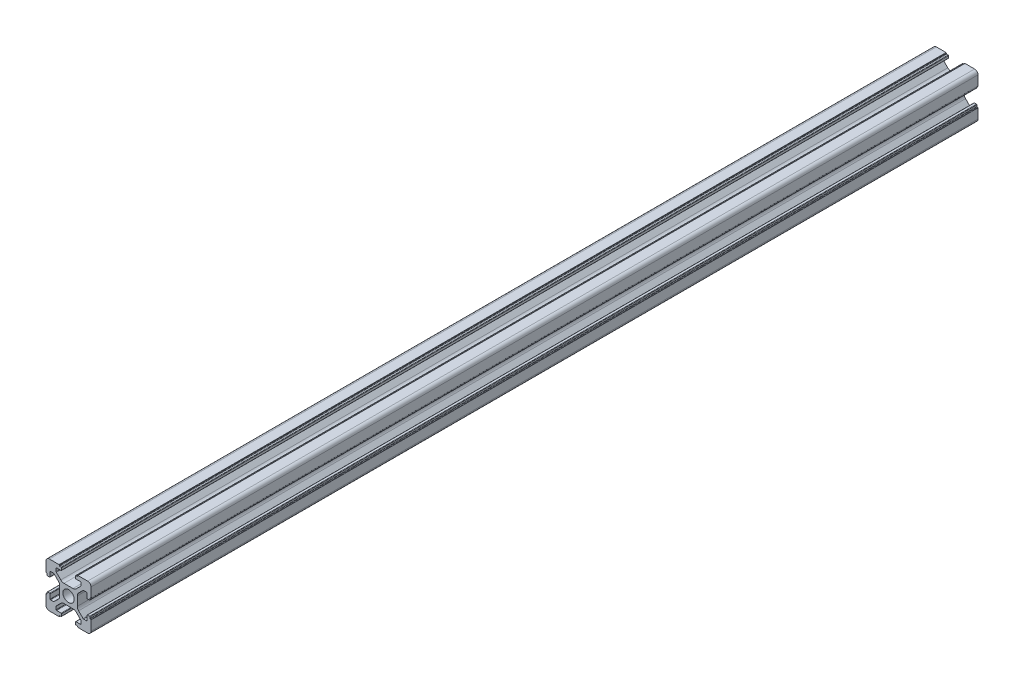
SolidWorks part; units mm, degrees
material "6063-T5"
ref_plane "Front Plane" through (0, 0, 0) normal (0, 0, 1) x (1, 0, 0)
ref_plane "Top Plane" through (0, 0, 0) normal (0, 1, 0) x (1, 0, 0)
ref_plane "Right Plane" through (0, 0, 0) normal (1, 0, 0) x (0, 0, -1)
sketch "Sketch1" plane through (0, 0, 0) normal (0, 0, -1) x (1, 0, 0)
  line L0 (1.5, 0) -> (5.8, 0)
  line L1 (20, 1.5) -> (20, 5.8)
  line L2 (18.5, 20) -> (14.2, 20)
  line L3 (0, 18.5) -> (0, 14.2)
  line L4 (14.2, 0) -> (18.5, 0)
  line L5 (13.3, 18.2) -> (15.3, 18.2)
  line L6 (20, 14.2) -> (20, 18.5)
  line L7 (0, 5.8) -> (0, 1.5)
  line L8 (6.7, 18.2) -> (4.7, 18.2)
  line L9 (1.8, 13.3) -> (1.8, 15.3)
  line L10 (19.3, 13.1) -> (18.4, 13.1)
  line L11 (19.3, 6.9) -> (18.4, 6.9)
  line L12 (6.9, 19.3) -> (6.9, 18.4)
  line L13 (13.1, 19.3) -> (13.1, 18.4)
  line L14 (0.7, 13.1) -> (1.6, 13.1)
  line L15 (0.7, 6.9) -> (1.6, 6.9)
  line L16 (13.4251, 14.4858) -> (15.4121, 16.4728)
  line L17 (14.4858, 13.4251) -> (16.4728, 15.4121)
  line L18 (14.4858, 6.5749) -> (16.4728, 4.5879)
  line L19 (13.4251, 5.5142) -> (15.4121, 3.5272)
  line L20 (6.5749, 5.5142) -> (4.5879, 3.5272)
  line L21 (5.5142, 6.5749) -> (3.5272, 4.5879)
  line L22 (5.5142, 13.4251) -> (3.5272, 15.4121)
  line L23 (6.5749, 14.4858) -> (4.5879, 16.4728)
  line L24 (6.9, 0.7) -> (6.9, 1.6)
  line L25 (13.1, 0.7) -> (13.1, 1.6)
  line L26 (5.8, 20) -> (1.5, 20)
  line L27 (1.8, 6.7) -> (1.8, 4.7)
  line L28 (6.7, 1.8) -> (4.7, 1.8)
  line L29 (13.3, 1.8) -> (15.3, 1.8)
  line L30 (18.2, 13.3) -> (18.2, 15.3)
  line L31 (18.2, 6.7) -> (18.2, 4.7)
  line L32 (2, 4.5) -> (3.3151, 4.5)
  line L33 (2, 15.5) -> (3.3151, 15.5)
  line L34 (4.5, 18) -> (4.5, 16.6849)
  line L35 (15.5, 18) -> (15.5, 16.6849)
  line L36 (18, 15.5) -> (16.6849, 15.5)
  line L37 (4.5, 2) -> (4.5, 3.3151)
  line L38 (15.5, 2) -> (15.5, 3.3151)
  line L39 (18, 4.5) -> (16.6849, 4.5)
  line L40 (7.9891, 13.9) -> (12.0109, 13.9)
  line L41 (7.9891, 6.1) -> (12.0109, 6.1)
  line L42 (13.9, 12.0109) -> (13.9, 7.9891)
  line L43 (6.1, 12.0109) -> (6.1, 7.9891)
  line L44 (19.5, 6.7) -> (19.5, 6.1)
  line L45 (5.9, 19.9) -> (5.9, 19.7)
  line L46 (6.1, 19.5) -> (6.7, 19.5)
  line L47 (14.1, 19.9) -> (14.1, 19.7)
  line L48 (13.9, 19.5) -> (13.3, 19.5)
  line L49 (0.1, 14.1) -> (0.3, 14.1)
  line L50 (0.5, 13.9) -> (0.5, 13.3)
  line L51 (0.1, 5.9) -> (0.3, 5.9)
  line L52 (0.5, 6.1) -> (0.5, 6.7)
  line L53 (19.9, 14.1) -> (19.7, 14.1)
  line L54 (19.5, 13.9) -> (19.5, 13.3)
  line L55 (19.7, 5.9) -> (19.9, 5.9)
  line L56 (14.1, 0.1) -> (14.1, 0.3)
  line L57 (13.9, 0.5) -> (13.3, 0.5)
  line L58 (6.7, 0.5) -> (6.1, 0.5)
  line L59 (5.9, 0.3) -> (5.9, 0.1)
  circle A0 centre (10, 10) radius 2.5
  arc A1 (18.5, 0) -> (20, 1.5) centre (18.5, 1.5) ccw
  arc A2 (1.5, 0) -> (0, 1.5) centre (1.5, 1.5) cw
  arc A3 (20, 18.5) -> (18.5, 20) centre (18.5, 18.5) ccw
  arc A4 (1.5, 20) -> (0, 18.5) centre (1.5, 18.5) ccw
  arc A5 (12.0109, 6.1) -> (13.4251, 5.5142) centre (12.0109, 4.1) cw
  arc A6 (13.9, 7.9891) -> (14.4858, 6.5749) centre (15.9, 7.9891) ccw
  arc A7 (13.9, 12.0109) -> (14.4858, 13.4251) centre (15.9, 12.0109) cw
  arc A8 (12.0109, 13.9) -> (13.4251, 14.4858) centre (12.0109, 15.9) ccw
  arc A9 (7.9891, 13.9) -> (6.5749, 14.4858) centre (7.9891, 15.9) cw
  arc A10 (6.1, 7.9891) -> (5.5142, 6.5749) centre (4.1, 7.9891) cw
  arc A11 (6.1, 12.0109) -> (5.5142, 13.4251) centre (4.1, 12.0109) ccw
  arc A12 (13.1, 1.6) -> (13.3, 1.8) centre (13.3, 1.6) cw
  arc A13 (6.9, 1.6) -> (6.7, 1.8) centre (6.7, 1.6) ccw
  arc A14 (6.1, 0.5) -> (5.9, 0.3) centre (6.1, 0.3) ccw
  arc A15 (6.7, 0.5) -> (6.9, 0.7) centre (6.7, 0.7) ccw
  arc A16 (1.6, 6.9) -> (1.8, 6.7) centre (1.6, 6.7) cw
  arc A17 (0.5, 6.7) -> (0.7, 6.9) centre (0.7, 6.7) cw
  arc A18 (0.5, 13.3) -> (0.7, 13.1) centre (0.7, 13.3) ccw
  arc A19 (1.6, 13.1) -> (1.8, 13.3) centre (1.6, 13.3) ccw
  arc A20 (6.7, 19.5) -> (6.9, 19.3) centre (6.7, 19.3) cw
  arc A21 (6.9, 18.4) -> (6.7, 18.2) centre (6.7, 18.4) cw
  arc A22 (13.1, 18.4) -> (13.3, 18.2) centre (13.3, 18.4) ccw
  arc A23 (13.3, 19.5) -> (13.1, 19.3) centre (13.3, 19.3) ccw
  arc A24 (18.4, 13.1) -> (18.2, 13.3) centre (18.4, 13.3) cw
  arc A25 (19.5, 13.3) -> (19.3, 13.1) centre (19.3, 13.3) cw
  arc A26 (19.5, 6.7) -> (19.3, 6.9) centre (19.3, 6.7) ccw
  arc A27 (14.1, 0.3) -> (13.9, 0.5) centre (13.9, 0.3) ccw
  arc A28 (19.5, 6.1) -> (19.7, 5.9) centre (19.7, 6.1) ccw
  arc A29 (5.9, 19.7) -> (6.1, 19.5) centre (6.1, 19.7) ccw
  arc A30 (14.1, 19.7) -> (13.9, 19.5) centre (13.9, 19.7) cw
  arc A31 (19.7, 14.1) -> (19.5, 13.9) centre (19.7, 13.9) ccw
  arc A32 (13.3, 0.5) -> (13.1, 0.7) centre (13.3, 0.7) cw
  arc A33 (0.3, 14.1) -> (0.5, 13.9) centre (0.3, 13.9) cw
  arc A34 (0.3, 5.9) -> (0.5, 6.1) centre (0.3, 6.1) ccw
  arc A35 (0, 5.8) -> (0.1, 5.9) centre (0.1, 5.8) cw
  arc A36 (5.9, 0.1) -> (5.8, 0) centre (5.8, 0.1) cw
  arc A37 (14.1, 0.1) -> (14.2, 0) centre (14.2, 0.1) ccw
  arc A38 (19.9, 5.9) -> (20, 5.8) centre (19.9, 5.8) cw
  arc A39 (20, 14.2) -> (19.9, 14.1) centre (19.9, 14.2) cw
  arc A40 (14.2, 20) -> (14.1, 19.9) centre (14.2, 19.9) ccw
  arc A41 (5.8, 20) -> (5.9, 19.9) centre (5.8, 19.9) cw
  arc A42 (0, 14.2) -> (0.1, 14.1) centre (0.1, 14.2) ccw
  arc A43 (18.4, 6.9) -> (18.2, 6.7) centre (18.4, 6.7) ccw
  arc A44 (1.8, 15.3) -> (2, 15.5) centre (2, 15.3) cw
  arc A45 (1.8, 4.7) -> (2, 4.5) centre (2, 4.7) ccw
  arc A46 (4.7, 1.8) -> (4.5, 2) centre (4.7, 2) cw
  arc A47 (15.3, 1.8) -> (15.5, 2) centre (15.3, 2) ccw
  arc A48 (18.2, 4.7) -> (18, 4.5) centre (18, 4.7) cw
  arc A49 (18.2, 15.3) -> (18, 15.5) centre (18, 15.3) ccw
  arc A50 (15.3, 18.2) -> (15.5, 18) centre (15.3, 18) cw
  arc A51 (4.7, 18.2) -> (4.5, 18) centre (4.7, 18) ccw
  arc A52 (7.9891, 6.1) -> (6.5749, 5.5142) centre (7.9891, 4.1) ccw
  arc A53 (3.3151, 15.5) -> (3.5272, 15.4121) centre (3.3151, 15.2) cw
  arc A54 (4.5, 16.6849) -> (4.5879, 16.4728) centre (4.8, 16.6849) ccw
  arc A55 (15.5, 16.6849) -> (15.4121, 16.4728) centre (15.2, 16.6849) cw
  arc A56 (16.6849, 15.5) -> (16.4728, 15.4121) centre (16.6849, 15.2) ccw
  arc A57 (16.6849, 4.5) -> (16.4728, 4.5879) centre (16.6849, 4.8) cw
  arc A58 (15.5, 3.3151) -> (15.4121, 3.5272) centre (15.2, 3.3151) ccw
  arc A59 (4.5, 3.3151) -> (4.5879, 3.5272) centre (4.8, 3.3151) cw
  arc A60 (3.3151, 4.5) -> (3.5272, 4.5879) centre (3.3151, 4.8) ccw
  point P67 (0, 0)
  point P125 (14.1, 19.5)
extrude "Boss-Extrude1" add sketch "Sketch1" along normal blind 394 contours L23 A54 L34 A51 L8 A21 L12 A20 L46 A29 L45 A41 L26 A4 L3 A42 L49 A33 L50 A18 L14 A19 L9 A44 L33 A53 L22 A11 L43 A10 L21 A60 L32 A45 L27 A16 L15 A17 L52 A34 L51 A35 L7 A2 L0 A36 L59 A14 L58 A15 L24 A13 L28 A46 L37 A59 L20 A52 L41 A5 L19 A58 L38 A47 L29 A12 L25 A32 L57 A27 L56 A37 L4 A1 L1 A38 L55 A28 L44 A26 L11 A43 L31 A48 L39 A57 L18 A6 L42 A7 L17 A56 L36 A49 L30 A24 L10 A25 L54 A31 L53 A39 L6 A3 L2 A40 L47 A30 L48 A23 L13 A22 L5 A50 L35 A55 L16 A8 L40 A9 | A0
